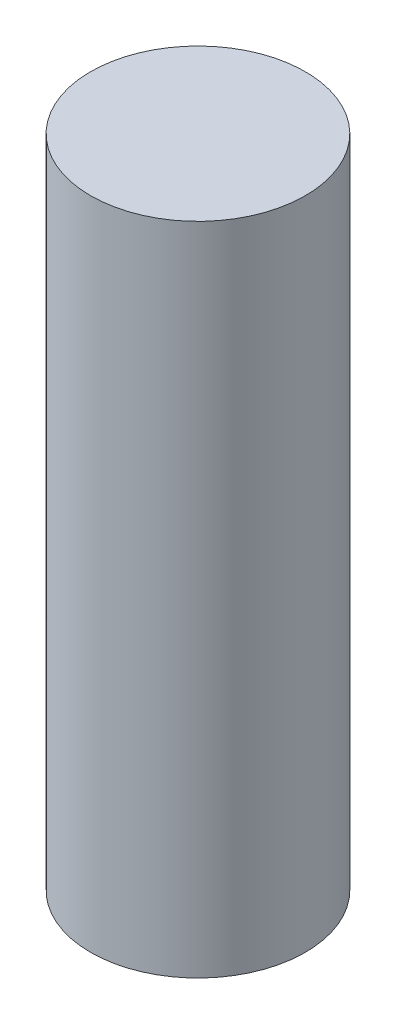
SolidWorks part; units mm, degrees
ref_plane "Plan de face" through (0, 0, 0) normal (0, 0, 1) x (1, 0, 0)
ref_plane "Plan de dessus" through (0, 0, 0) normal (0, 1, 0) x (1, 0, 0)
ref_plane "Plan de droite" through (0, 0, 0) normal (1, 0, 0) x (0, 0, -1)
sketch "Esquisse1" plane through (0, 0, 0) normal (0, 1, 0) x (1, 0, 0)
  circle A0 centre (0, 0) radius 2.95
  dimension "D1" = 5.9
extrude "Boss.-Extru.1" add sketch "Esquisse1" along normal mid plane 18
sketch "Esquisse2" plane through (0, 0, 0) normal (0, 1, 0) x (1, 0, 0)
  point P0 (0, 0)
